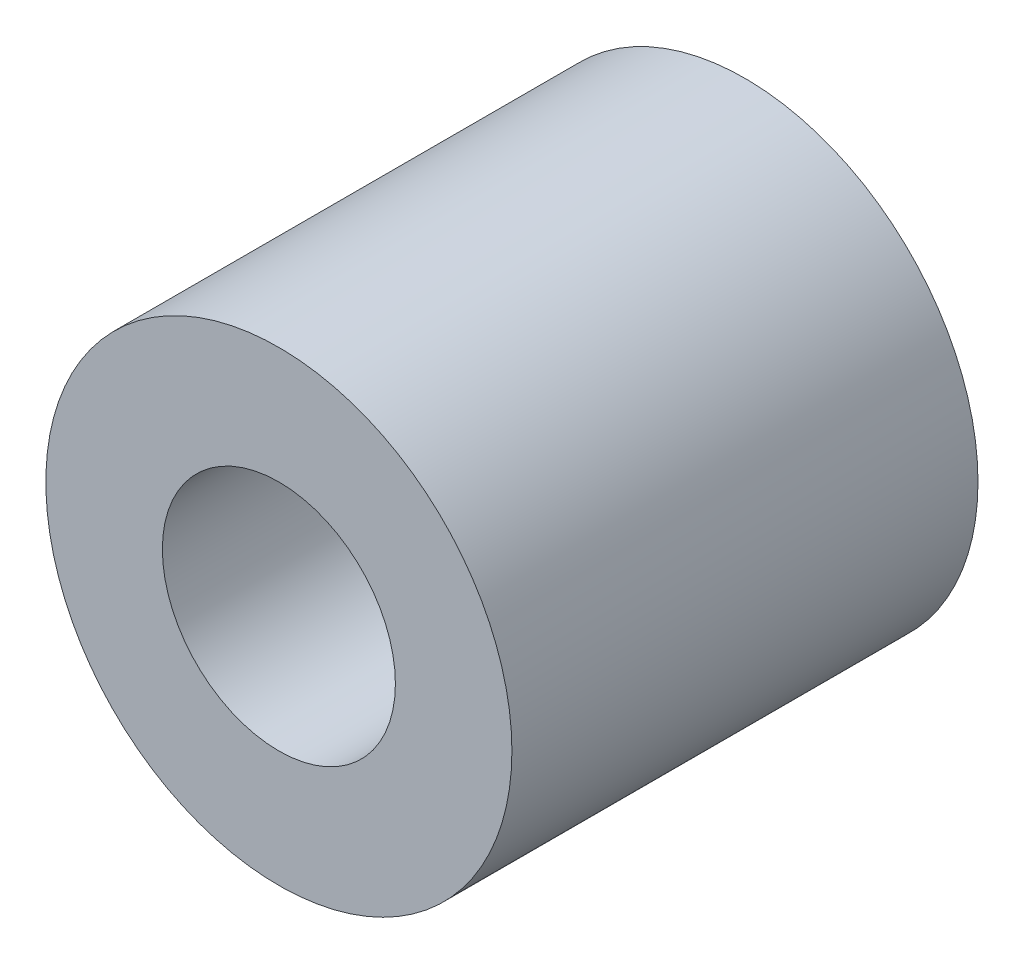
SolidWorks part; units mm, degrees
material "合金钢"
ref_plane "前视基准面" through (0, 0, 0) normal (0, 0, 1) x (1, 0, 0)
ref_plane "上视基准面" through (0, 0, 0) normal (0, 1, 0) x (1, 0, 0)
ref_plane "右视基准面" through (0, 0, 0) normal (1, 0, 0) x (0, 0, -1)
sketch "草图1" plane through (0, 0, 0) normal (0, 0, 1) x (1, 0, 0)
  circle A0 centre (0, 0) radius 8
  dimension "D1" = 16
extrude "凸台-拉伸1" add sketch "草图1" along normal blind 16
sketch "草图2" plane through (0, 0, 0) normal (0, 0, -1) x (-1, 0, 0)
  circle A0 centre (0, 0) radius 2.5
  dimension "D1" = 5
extrude "切除-拉伸1" cut sketch "草图2" against normal blind 16
sketch "草图3" plane through (0, 0, 16) normal (0, 0, 1) x (1, 0, 0)
  circle A0 centre (0, 0) radius 4
  dimension "D1" = 8
extrude "切除-拉伸2" cut sketch "草图3" against normal blind 8
